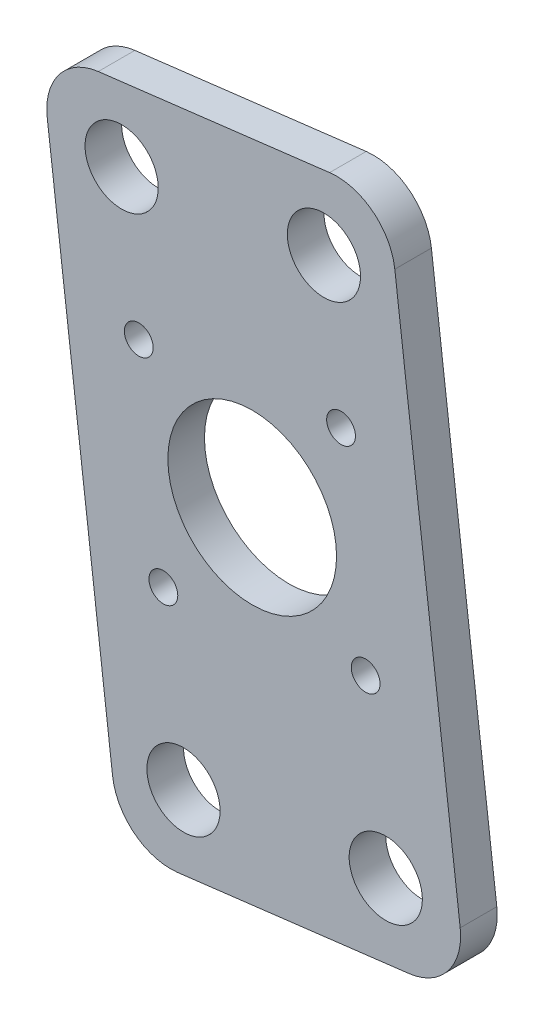
SolidWorks part; units mm, degrees
ref_plane "Front Plane" through (0, 0, 0) normal (0, 0, 1) x (1, 0, 0)
ref_plane "Top Plane" through (0, 0, 0) normal (0, 1, 0) x (1, 0, 0)
ref_plane "Right Plane" through (0, 0, 0) normal (1, 0, 0) x (0, 0, -1)
sketch "Sketch1" plane through (0, 0, 0) normal (0, 0, 1) x (1, 0, 0)
  line L12 (-108.1848, -135.7641) -> (-102.5125, -182.4105)
  line L15 (-96.8564, -186.8401) -> (-76.7866, -184.3996)
  line L16 (-72.3569, -178.7435) -> (-78.0293, -132.0971)
  line L17 (-83.6853, -127.6675) -> (-103.7552, -130.108)
  line L18 (-82.6932, -146.3471) -> (-80.5593, -163.8955) construction
  line L19 (-90.4004, -156.1882) -> (-93.9794, -126.7566) construction
  line L20 (-90.4004, -156.1882) -> (-86.8215, -185.6198) construction
  line L21 (-85.283, -160.196) -> (-85.4799, -160.0418)
  line L22 (-95.321, -152.3346) -> (-95.5178, -152.1805)
  arc A0 (-97.1236, -166.8001) -> (-99.0918, -165.2587) centre (-98.1077, -166.0294) ccw
  arc A1 (-99.0918, -165.2587) -> (-97.1236, -166.8001) centre (-98.1077, -166.0294) ccw
  arc A2 (-81.5434, -163.1247) -> (-79.5752, -164.6662) centre (-80.5593, -163.8955) ccw
  arc A3 (-79.5752, -164.6662) -> (-81.5434, -163.1247) centre (-80.5593, -163.8955) ccw
  arc A4 (-81.7091, -147.1178) -> (-83.6773, -145.5763) centre (-82.6932, -146.3471) ccw
  arc A5 (-83.6773, -145.5763) -> (-81.7091, -147.1178) centre (-82.6932, -146.3471) ccw
  arc A6 (-101.2257, -147.7103) -> (-99.2575, -149.2517) centre (-100.2416, -148.481) ccw
  arc A7 (-99.2575, -149.2517) -> (-101.2257, -147.7103) centre (-100.2416, -148.481) ccw
  circle A25 centre (-101.7279, -136.2583) radius 3.175
  circle A26 centre (-84.1795, -134.1244) radius 3.175
  circle A27 centre (-78.8138, -178.2493) radius 3.175
  circle A28 centre (-96.3622, -180.3832) radius 3.175
  arc A29 (-102.5125, -182.4105) -> (-96.8564, -186.8401) centre (-97.4696, -181.7973) ccw
  arc A30 (-76.7866, -184.3996) -> (-72.3569, -178.7435) centre (-77.3998, -179.3567) ccw
  arc A31 (-78.0293, -132.0971) -> (-83.6853, -127.6675) centre (-83.0721, -132.7103) ccw
  arc A32 (-108.1848, -135.7641) -> (-103.7552, -130.108) centre (-103.1419, -135.1509) cw
  arc A33 (-85.4799, -160.0418) -> (-95.321, -152.3346) centre (-90.4004, -156.1882) ccw
  circle A34 centre (-90.4004, -156.1882) radius 7.3172
  arc A35 (-94.4082, -161.3056) -> (-85.283, -160.196) centre (-90.4004, -156.1882) ccw
  arc A36 (-95.321, -152.3346) -> (-85.4799, -160.0418) centre (-90.4004, -156.1882) ccw
  arc A37 (-95.5178, -152.1805) -> (-94.4082, -161.3056) centre (-90.4004, -156.1882) ccw
  point P32 (0, 0)
  dimension "D6" = 6.35
  dimension "D8" = 6.35
  dimension "D10" = 6.35
  dimension "D15" = 5.08
  dimension "D2" = 6.35
  dimension "D5" = 6.35
  dimension "D7" = 6.35
  dimension "D9" = 6.35
  dimension "D14" = 6.35
  dimension "D1" = 6.35
  dimension "D3" = 6.35
  dimension "D4" = 6.35
  dimension "D11" = 6.35
  dimension "D12" = 6.35
  dimension "D13" = 6.35
extrude "Boss-Extrude2" add sketch "Sketch1" along normal blind 3.175 contours A32 L12 A29 L15 A30 L16 A31 L17 A34 A28 A27 A26 A25 A7 A6 A5 A4 A3 A2 A1 A0
